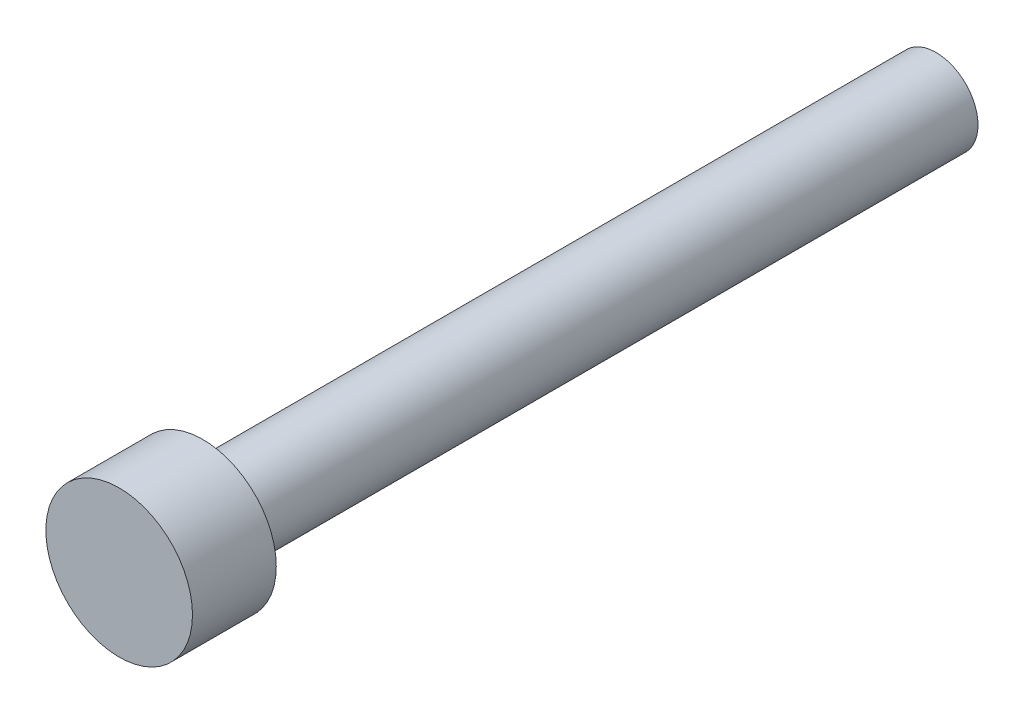
SolidWorks part; units mm, degrees
ref_plane "Front Plane" through (0, 0, 0) normal (0, 0, 1) x (1, 0, 0)
ref_plane "Top Plane" through (0, 0, 0) normal (0, 1, 0) x (1, 0, 0)
ref_plane "Right Plane" through (0, 0, 0) normal (1, 0, 0) x (0, 0, -1)
sketch "Shank_nominal_thread_envelope_profile" plane through (0, 0, 0) normal (0, 0, 1) x (1, 0, 0)
  circle A0 centre (0, 0) radius 2
  dimension "D1" = 4
extrude "Shank_nominal_thread_envelope" add sketch "Shank_nominal_thread_envelope_profile" along normal blind 35 from offset 35
sketch "Socket_head_envelope_profile" plane through (0, 0, 0) normal (0, 0, 1) x (1, 0, 0)
  circle A0 centre (0, 0) radius 3.5
  dimension "D1" = 7
extrude "Socket_head_envelope" add sketch "Socket_head_envelope_profile" along normal blind 4
